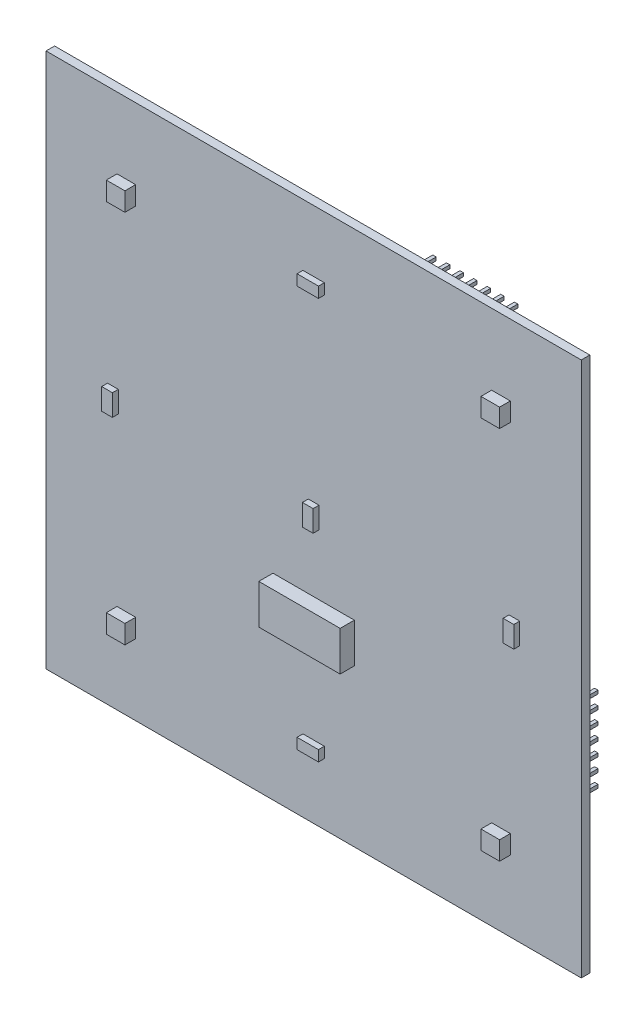
SolidWorks part; units mm, degrees
ref_plane "正面" through (0, 0, 0) normal (0, 0, 1) x (1, 0, 0)
ref_plane "平面" through (0, 0, 0) normal (0, 1, 0) x (1, 0, 0)
ref_plane "右側面" through (0, 0, 0) normal (1, 0, 0) x (0, 0, -1)
sketch "ｽｹｯﾁ1" plane through (0, 0, 0) normal (0, 0, 1) x (1, 0, 0)
  line L0 (-50, 0) -> (50, 0) construction
  line L1 (-50, 50) -> (50, 50)
  line L2 (-50, 50) -> (-50, -50)
  line L3 (-50, -50) -> (50, -50)
  line L4 (50, 50) -> (50, -50)
  line L5 (0, -50) -> (0, 50) construction
  point P8 (0, 0)
  dimension "D1" = 100
  dimension "D2" = 100
  dimension "D3" = 0
  dimension "D4" = 0
extrude "ﾎﾞｽ - 押し出し1" add sketch "ｽｹｯﾁ1" along normal blind 1.6
sketch "ｽｹｯﾁ4" plane through (0, 0, 0) normal (0, 0, -1) x (-1, 0, 0)
  line L0 (-50, -50) -> (-50, 50) construction
  line L1 (11.11, -41.35) -> (28.89, -41.35)
  line L2 (11.11, -41.35) -> (11.11, -43.85)
  line L3 (11.11, -43.85) -> (28.89, -43.85)
  line L4 (28.89, -41.35) -> (28.89, -43.85)
  line L5 (50, -50) -> (-50, -50) construction
  line L6 (50, 50) -> (50, -50) construction
  line L8 (-43.85, -11.11) -> (-41.35, -11.11)
  line L9 (-43.85, -11.11) -> (-43.85, -28.89)
  line L10 (-43.85, -28.89) -> (-41.35, -28.89)
  line L11 (-41.35, -11.11) -> (-41.35, -28.89)
  line L12 (-28.89, 43.85) -> (-11.11, 43.85)
  line L13 (-28.89, 43.85) -> (-28.89, 41.35)
  line L14 (-28.89, 41.35) -> (-11.11, 41.35)
  line L15 (-11.11, 43.85) -> (-11.11, 41.35)
  line L16 (-50, 50) -> (50, 50) construction
  line L18 (41.35, 28.89) -> (43.85, 28.89)
  line L19 (41.35, 28.89) -> (41.35, 11.11)
  line L20 (41.35, 11.11) -> (43.85, 11.11)
  line L21 (43.85, 28.89) -> (43.85, 11.11)
  point P4 (28.89, -42.6)
  point P7 (20, -43.85)
  point P14 (-43.85, -20)
  point P15 (-42.6, -28.89)
  point P22 (-28.89, 42.6)
  point P25 (43.85, 20)
  point P26 (-20, 43.85)
  point P31 (42.6, 28.89)
  dimension "D1" = 7.4
  dimension "D2" = 30
  dimension "D3" = 2.5
  dimension "D4" = 17.78
  dimension "D5" = 2.5
  dimension "D6" = 17.78
  dimension "D7" = 30
  dimension "D8" = 7.4
  dimension "D9" = 2.5
  dimension "D10" = 7.4
  dimension "D11" = 30
  dimension "D12" = 17.78
  dimension "D13" = 17.78
  dimension "D14" = 2.5
  dimension "D15" = 30
  dimension "D16" = 7.4
extrude "ﾎﾞｽ - 押し出し2" add sketch "ｽｹｯﾁ4" along normal blind 2.5
sketch "ｽｹｯﾁ5" plane through (0, 0, -2.5) normal (0, 0, -1) x (-1, 0, 0)
  line L1 (-20.32, 42.92) -> (-19.68, 42.92)
  line L2 (-20.32, 42.92) -> (-20.32, 42.28)
  line L3 (-20.32, 42.28) -> (-19.68, 42.28)
  line L4 (-19.68, 42.92) -> (-19.68, 42.28)
  line L5 (43.85, 28.89) -> (41.35, 28.89) construction
  line L6 (-11.11, 43.85) -> (-28.89, 43.85) construction
  line L7 (-28.89, 43.85) -> (-28.89, 41.35) construction
  line L8 (-43.85, -28.89) -> (-41.35, -28.89) construction
  line L9 (-17.78, 42.92) -> (-17.14, 42.92)
  line L10 (-17.78, 42.92) -> (-17.78, 42.28)
  line L11 (-17.78, 42.28) -> (-17.14, 42.28)
  line L12 (-17.14, 42.92) -> (-17.14, 42.28)
  line L13 (-15.24, 42.92) -> (-14.6, 42.92)
  line L14 (-15.24, 42.92) -> (-15.24, 42.28)
  line L15 (-15.24, 42.28) -> (-14.6, 42.28)
  line L16 (-14.6, 42.92) -> (-14.6, 42.28)
  line L17 (-12.7, 42.92) -> (-12.06, 42.92)
  line L18 (-12.7, 42.92) -> (-12.7, 42.28)
  line L19 (-12.7, 42.28) -> (-12.06, 42.28)
  line L20 (-12.06, 42.92) -> (-12.06, 42.28)
  line L21 (-22.86, 42.92) -> (-22.22, 42.92)
  line L22 (-22.86, 42.92) -> (-22.86, 42.28)
  line L23 (-22.86, 42.28) -> (-22.22, 42.28)
  line L24 (-22.22, 42.92) -> (-22.22, 42.28)
  line L25 (-25.4, 42.92) -> (-24.76, 42.92)
  line L26 (-25.4, 42.92) -> (-25.4, 42.28)
  line L27 (-25.4, 42.28) -> (-24.76, 42.28)
  line L28 (-24.76, 42.92) -> (-24.76, 42.28)
  line L29 (-27.94, 42.92) -> (-27.3, 42.92)
  line L30 (-27.94, 42.92) -> (-27.94, 42.28)
  line L31 (-27.94, 42.28) -> (-27.3, 42.28)
  line L32 (-27.3, 42.92) -> (-27.3, 42.28)
  line L33 (-42.92, -19.68) -> (-42.28, -19.68)
  line L34 (-42.92, -19.68) -> (-42.92, -20.32)
  line L35 (-42.92, -20.32) -> (-42.28, -20.32)
  line L36 (-42.28, -19.68) -> (-42.28, -20.32)
  line L37 (-43.85, -11.11) -> (-43.85, -28.89) construction
  line L38 (43.85, 11.11) -> (43.85, 28.89) construction
  line L39 (-42.92, -22.22) -> (-42.28, -22.22)
  line L40 (-42.92, -22.22) -> (-42.92, -22.86)
  line L41 (-42.92, -22.86) -> (-42.28, -22.86)
  line L42 (-42.28, -22.22) -> (-42.28, -22.86)
  line L44 (42.28, 19.68) -> (42.92, 19.68)
  line L45 (-42.92, -24.76) -> (-42.28, -24.76)
  line L46 (-42.92, -24.76) -> (-42.92, -25.4)
  line L47 (-42.92, -25.4) -> (-42.28, -25.4)
  line L48 (-42.28, -24.76) -> (-42.28, -25.4)
  line L49 (-42.92, -27.3) -> (-42.28, -27.3)
  line L50 (-42.92, -27.3) -> (-42.92, -27.94)
  line L51 (-42.92, -27.94) -> (-42.28, -27.94)
  line L52 (-42.28, -27.3) -> (-42.28, -27.94)
  line L53 (-42.92, -17.14) -> (-42.28, -17.14)
  line L54 (-42.92, -17.14) -> (-42.92, -17.78)
  line L55 (-42.92, -17.78) -> (-42.28, -17.78)
  line L56 (-42.28, -17.14) -> (-42.28, -17.78)
  line L57 (-42.92, -14.6) -> (-42.28, -14.6)
  line L58 (-42.92, -14.6) -> (-42.92, -15.24)
  line L59 (-42.92, -15.24) -> (-42.28, -15.24)
  line L60 (-42.28, -14.6) -> (-42.28, -15.24)
  line L61 (-42.92, -12.06) -> (-42.28, -12.06)
  line L62 (-42.92, -12.06) -> (-42.92, -12.7)
  line L63 (-42.92, -12.7) -> (-42.28, -12.7)
  line L64 (-42.28, -12.06) -> (-42.28, -12.7)
  line L69 (42.28, 19.68) -> (42.28, 20.32)
  line L70 (11.11, -43.85) -> (28.89, -43.85) construction
  line L71 (42.28, 17.78) -> (42.92, 17.78)
  line L72 (42.28, 20.32) -> (42.92, 20.32)
  line L73 (42.92, 19.68) -> (42.92, 20.32)
  line L75 (42.28, 17.78) -> (42.28, 17.14)
  line L76 (42.28, 17.14) -> (42.92, 17.14)
  line L77 (42.92, 17.78) -> (42.92, 17.14)
  line L78 (42.28, 15.24) -> (42.92, 15.24)
  line L79 (42.28, 15.24) -> (42.28, 14.6)
  line L80 (42.28, 14.6) -> (42.92, 14.6)
  line L81 (42.92, 15.24) -> (42.92, 14.6)
  line L82 (42.28, 12.7) -> (42.92, 12.7)
  line L83 (42.28, 12.7) -> (42.28, 12.06)
  line L84 (42.28, 12.06) -> (42.92, 12.06)
  line L85 (42.92, 12.7) -> (42.92, 12.06)
  line L86 (42.28, 22.86) -> (42.92, 22.86)
  line L87 (42.28, 22.86) -> (42.28, 22.22)
  line L88 (42.28, 22.22) -> (42.92, 22.22)
  line L89 (42.92, 22.86) -> (42.92, 22.22)
  line L90 (42.28, 25.4) -> (42.92, 25.4)
  line L91 (42.28, 25.4) -> (42.28, 24.76)
  line L92 (42.28, 24.76) -> (42.92, 24.76)
  line L93 (42.92, 25.4) -> (42.92, 24.76)
  line L94 (42.28, 27.94) -> (42.92, 27.94)
  line L95 (42.28, 27.94) -> (42.28, 27.3)
  line L96 (42.28, 27.3) -> (42.92, 27.3)
  line L97 (42.92, 27.94) -> (42.92, 27.3)
  line L98 (19.68, -42.28) -> (20.32, -42.28)
  line L99 (19.68, -42.28) -> (19.68, -42.92)
  line L100 (19.68, -42.92) -> (20.32, -42.92)
  line L101 (20.32, -42.28) -> (20.32, -42.92)
  line L102 (11.11, -41.35) -> (11.11, -43.85) construction
  line L104 (17.14, -42.28) -> (17.78, -42.28)
  line L105 (17.14, -42.28) -> (17.14, -42.92)
  line L106 (17.14, -42.92) -> (17.78, -42.92)
  line L107 (17.78, -42.28) -> (17.78, -42.92)
  line L108 (14.6, -42.28) -> (15.24, -42.28)
  line L109 (14.6, -42.28) -> (14.6, -42.92)
  line L110 (14.6, -42.92) -> (15.24, -42.92)
  line L111 (15.24, -42.28) -> (15.24, -42.92)
  line L112 (12.06, -42.28) -> (12.7, -42.28)
  line L113 (12.06, -42.28) -> (12.06, -42.92)
  line L114 (12.06, -42.92) -> (12.7, -42.92)
  line L115 (12.7, -42.28) -> (12.7, -42.92)
  line L116 (22.22, -42.28) -> (22.86, -42.28)
  line L117 (22.22, -42.28) -> (22.22, -42.92)
  line L118 (22.22, -42.92) -> (22.86, -42.92)
  line L119 (22.86, -42.28) -> (22.86, -42.92)
  line L120 (24.76, -42.28) -> (25.4, -42.28)
  line L121 (24.76, -42.28) -> (24.76, -42.92)
  line L122 (24.76, -42.92) -> (25.4, -42.92)
  line L123 (25.4, -42.28) -> (25.4, -42.92)
  line L124 (27.3, -42.28) -> (27.94, -42.28)
  line L125 (27.3, -42.28) -> (27.3, -42.92)
  line L126 (27.3, -42.92) -> (27.94, -42.92)
  line L127 (27.94, -42.28) -> (27.94, -42.92)
  point P4 (-20, 42.92)
  point P7 (-20, 43.85)
  point P8 (-20.32, 42.6)
  point P11 (-28.89, 42.6)
  point P16 (-20, 42.28)
  point P17 (-17.46, 42.28)
  point P22 (-14.92, 42.28)
  point P27 (-12.38, 42.28)
  point P40 (-22.54, 42.28)
  point P41 (-25.08, 42.28)
  point P42 (-27.62, 42.28)
  point P47 (-42.6, -20.32)
  point P50 (-42.6, -28.89)
  point P53 (-42.92, -20)
  point P54 (-43.85, -20)
  point P59 (-42.28, -22.54)
  point P60 (-42.28, -20)
  point P61 (-42.28, -25.08)
  point P70 (-42.28, -27.62)
  point P83 (-42.28, -17.46)
  point P84 (-42.28, -14.92)
  point P85 (-42.28, -12.38)
  point P90 (42.6, 19.68)
  point P93 (42.6, 28.89)
  point P94 (42.92, 20)
  point P97 (43.85, 20)
  point P110 (42.28, 12.38)
  point P111 (42.28, 14.92)
  point P112 (42.28, 17.46)
  point P113 (42.28, 20)
  point P126 (42.28, 22.54)
  point P127 (42.28, 25.08)
  point P128 (42.28, 27.62)
  point P133 (20, -42.92)
  point P136 (20, -43.85)
  point P139 (11.11, -42.6)
  point P140 (19.68, -42.6)
  point P165 (17.46, -42.28)
  point P166 (20, -42.28)
  point P167 (14.92, -42.28)
  point P168 (12.38, -42.28)
  point P169 (22.54, -42.28)
  point P170 (25.08, -42.28)
  point P171 (27.62, -42.28)
  point P173 (12.06, -42.6)
  point P174 (14.6, -42.6)
  point P175 (17.14, -42.6)
  point P176 (22.22, -42.6)
  point P177 (24.76, -42.6)
  point P178 (27.3, -42.6)
  point P179 (-42.6, -27.3)
  point P180 (-42.6, -24.76)
  point P181 (-42.6, -22.22)
  point P182 (-42.6, -19.68)
  point P183 (-42.6, -17.14)
  point P184 (-42.6, -14.6)
  point P185 (-42.6, -12.06)
  point P186 (-27.94, 42.6)
  point P187 (-25.4, 42.6)
  point P188 (-22.86, 42.6)
  point P189 (-17.78, 42.6)
  point P190 (-15.24, 42.6)
  point P191 (-12.7, 42.6)
  point P192 (42.6, 15.24)
  point P193 (42.6, 17.78)
  point P194 (42.6, 20.32)
  point P195 (42.6, 22.86)
  point P196 (42.6, 25.4)
  point P197 (42.6, 27.94)
  point P198 (42.6, 12.7)
  dimension "D1" = 0.64
  dimension "D2" = 0.64
  dimension "D3" = 0.64
  dimension "D4" = 0.64
  dimension "D5" = 2.54
  dimension "D6" = 0.64
  dimension "D7" = 2.54
  dimension "D8" = 0.64
  dimension "D9" = 0.64
  dimension "D10" = 0.64
  dimension "D11" = 2.54
  dimension "D12" = 0.64
  dimension "D13" = 0.64
  dimension "D14" = 0.64
  dimension "D15" = 2.54
  dimension "D16" = 0.64
  dimension "D17" = 0.64
  dimension "D18" = 0.64
  dimension "D19" = 2.54
  dimension "D20" = 2.54
  dimension "D21" = 0.64
  dimension "D22" = 0.64
  dimension "D23" = 0.64
  dimension "D24" = 0.64
  dimension "D25" = 2.54
  dimension "D26" = 0.64
  dimension "D27" = 2.54
  dimension "D28" = 0.64
  dimension "D29" = 2.54
  dimension "D30" = 0.64
  dimension "D31" = 0.64
  dimension "D32" = 0.64
  dimension "D33" = 0.64
  dimension "D34" = 2.54
  dimension "D35" = 2.54
  dimension "D36" = 0.64
  dimension "D37" = 0.64
  dimension "D38" = 0.64
  dimension "D39" = 2.54
  dimension "D40" = 0.64
  dimension "D41" = 0.64
  dimension "D42" = 0.64
  dimension "D43" = 0.64
  dimension "D44" = 0.64
  dimension "D45" = 0.64
  dimension "D46" = 2.54
  dimension "D47" = 2.54
  dimension "D48" = 2.54
  dimension "D49" = 2.54
  dimension "D50" = 0.64
  dimension "D51" = 0.64
  dimension "D52" = 0.64
  dimension "D53" = 0.64
  dimension "D54" = 2.54
  dimension "D55" = 0.64
  dimension "D56" = 0.64
  dimension "D57" = 2.54
  dimension "D58" = 0.64
  dimension "D59" = 0.64
  dimension "D60" = 0.64
  dimension "D61" = 0.64
  dimension "D62" = 0.64
  dimension "D63" = 2.54
  dimension "D64" = 2.54
  dimension "D65" = 2.54
  dimension "D66" = 0.64
  dimension "D67" = 0.64
  dimension "D68" = 0.64
  dimension "D69" = 0.64
  dimension "D70" = 0.64
  dimension "D71" = 0.64
  dimension "D72" = 2.54
  dimension "D73" = 2.54
  dimension "D74" = 2.54
  dimension "D75" = 0.64
  dimension "D76" = 0.64
  dimension "D77" = 0.64
  dimension "D78" = 0.64
  dimension "D79" = 0.64
  dimension "D80" = 0.64
extrude "ﾎﾞｽ - 押し出し3" add sketch "ｽｹｯﾁ5" along normal blind 6.1
sketch "ｽｹｯﾁ6" plane through (0, 0, 1.6) normal (0, 0, 1) x (1, 0, 0)
  line L0 (-50, -50) -> (50, -50) construction
  line L1 (-36.74, -33.26) -> (-33.26, -33.26)
  line L2 (-36.74, -33.26) -> (-36.74, -36.74)
  line L3 (-36.74, -36.74) -> (-33.26, -36.74)
  line L4 (-33.26, -33.26) -> (-33.26, -36.74)
  line L5 (-50, 50) -> (-50, -50) construction
  line L6 (50, 50) -> (-50, 50) construction
  line L7 (-36.74, 36.74) -> (-33.26, 36.74)
  line L8 (-36.74, 36.74) -> (-36.74, 33.26)
  line L9 (-36.74, 33.26) -> (-33.26, 33.26)
  line L10 (-33.26, 36.74) -> (-33.26, 33.26)
  line L11 (50, -50) -> (50, 50) construction
  line L12 (33.26, -33.26) -> (36.74, -33.26)
  line L13 (33.26, -33.26) -> (33.26, -36.74)
  line L14 (33.26, -36.74) -> (36.74, -36.74)
  line L15 (36.74, -33.26) -> (36.74, -36.74)
  line L17 (33.26, 36.74) -> (36.74, 36.74)
  line L18 (33.26, 36.74) -> (33.26, 33.26)
  line L19 (33.26, 33.26) -> (36.74, 33.26)
  line L20 (36.74, 36.74) -> (36.74, 33.26)
  point P4 (-36.74, -35)
  point P7 (-35, -36.74)
  point P14 (-36.74, 35)
  point P17 (-35, 36.74)
  point P22 (35, -36.74)
  point P25 (36.74, -35)
  point P30 (35, 36.74)
  point P31 (36.74, 35)
  dimension "D1" = 3.48
  dimension "D2" = 3.48
  dimension "D3" = 15
  dimension "D4" = 15
  dimension "D5" = 3.48
  dimension "D6" = 3.48
  dimension "D7" = 15
  dimension "D8" = 15
  dimension "D9" = 15
  dimension "D10" = 15
  dimension "D11" = 3.48
  dimension "D12" = 3.48
  dimension "D13" = 15
  dimension "D14" = 15
  dimension "D15" = 3.48
  dimension "D16" = 3.48
extrude "ﾎﾞｽ - 押し出し4" add sketch "ｽｹｯﾁ6" along normal blind 2
sketch "ｽｹｯﾁ7" plane through (0, 0, 1.6) normal (0, 0, 1) x (1, 0, 0)
  line L0 (-50, -50) -> (50, -50) construction
  line L1 (-38.5, 2) -> (-36.5, 2)
  line L2 (-38.5, 2) -> (-38.5, -2)
  line L3 (-38.5, -2) -> (-36.5, -2)
  line L4 (-36.5, 2) -> (-36.5, -2)
  line L5 (-50, 50) -> (-50, -50) construction
  line L6 (50, -50) -> (50, 50) construction
  line L7 (36.5, 2) -> (38.5, 2)
  line L8 (36.5, 2) -> (36.5, -2)
  line L9 (36.5, -2) -> (38.5, -2)
  line L10 (38.5, 2) -> (38.5, -2)
  line L11 (50, 50) -> (-50, 50) construction
  line L12 (-2, 38.5) -> (2, 38.5)
  line L13 (-2, 38.5) -> (-2, 36.5)
  line L14 (-2, 36.5) -> (2, 36.5)
  line L15 (2, 38.5) -> (2, 36.5)
  line L17 (-2, -36.5) -> (2, -36.5)
  line L18 (-2, -36.5) -> (-2, -38.5)
  line L19 (-2, -38.5) -> (2, -38.5)
  line L20 (2, -36.5) -> (2, -38.5)
  line L21 (-1, 2) -> (1, 2)
  line L22 (-1, 2) -> (-1, -2)
  line L23 (-1, -2) -> (1, -2)
  line L24 (1, 2) -> (1, -2)
  point P4 (-38.5, 0)
  point P7 (-37.5, -2)
  point P14 (37.5, 2)
  point P17 (38.5, 0)
  point P22 (-2, 37.5)
  point P25 (0, 38.5)
  point P30 (-2, -37.5)
  point P31 (0, -38.5)
  point P36 (1, 0)
  point P37 (36.5, 0)
  point P38 (0, 36.5)
  point P39 (0, 2)
  dimension "D1" = 4
  dimension "D2" = 2
  dimension "D3" = 50
  dimension "D4" = 12.5
  dimension "D5" = 4
  dimension "D6" = 2
  dimension "D7" = 12.5
  dimension "D8" = 50
  dimension "D9" = 4
  dimension "D10" = 2
  dimension "D11" = 12.5
  dimension "D12" = 50
  dimension "D13" = 4
  dimension "D14" = 2
  dimension "D15" = 12.5
  dimension "D16" = 50
  dimension "D17" = 4
  dimension "D18" = 2
extrude "ﾎﾞｽ - 押し出し5" add sketch "ｽｹｯﾁ7" along normal blind 1.1
sketch "ｽｹｯﾁ8" plane through (0, 0, 1.6) normal (0, 0, 1) x (1, 0, 0)
  line L0 (-50, -50) -> (50, -50) construction
  line L1 (-7.6, -13.3) -> (7.6, -13.3)
  line L2 (-7.6, -13.3) -> (-7.6, -20.7)
  line L3 (-7.6, -20.7) -> (7.6, -20.7)
  line L4 (7.6, -13.3) -> (7.6, -20.7)
  point P4 (-7.6, -17)
  point P7 (0, -50)
  point P8 (0, -20.7)
  dimension "D1" = 7.4
  dimension "D2" = 15.2
  dimension "D3" = 33
extrude "ﾎﾞｽ - 押し出し6" add sketch "ｽｹｯﾁ8" along normal blind 2.65
sketch "ｽｹｯﾁ9" plane through (0, 0, 0) normal (0, 0, -1) x (-1, 0, 0)
  line L1 (-4.61, 19.83) -> (3.01, 19.83)
  line L2 (-4.61, 19.83) -> (-4.61, 17.33)
  line L3 (-4.61, 17.33) -> (3.01, 17.33)
  line L4 (3.01, 19.83) -> (3.01, 17.33)
  line L5 (50, 50) -> (50, -50) construction
  line L6 (50, -50) -> (-50, -50) construction
  point P4 (-0.8, 19.83)
  point P7 (3.01, 18.58)
  dimension "D1" = 7.62
  dimension "D2" = 2.5
  dimension "D3" = 50.8
  dimension "D4" = 68.58
extrude "ﾎﾞｽ - 押し出し7" add sketch "ｽｹｯﾁ9" along normal blind 2.5
sketch "ｽｹｯﾁ11" plane through (0, 0, -2.5) normal (0, 0, -1) x (-1, 0, 0)
  line L0 (3.01, 19.83) -> (-4.61, 19.83) construction
  line L1 (-1.12, 18.9) -> (-0.48, 18.9)
  line L2 (-1.12, 18.9) -> (-1.12, 18.26)
  line L3 (-1.12, 18.26) -> (-0.48, 18.26)
  line L4 (-0.48, 18.9) -> (-0.48, 18.26)
  line L5 (-4.61, 19.83) -> (-4.61, 17.33) construction
  line L7 (-3.66, 18.9) -> (-3.02, 18.9)
  line L8 (-3.66, 18.9) -> (-3.66, 18.26)
  line L9 (-3.66, 18.26) -> (-3.02, 18.26)
  line L10 (-3.02, 18.9) -> (-3.02, 18.26)
  line L11 (1.42, 18.9) -> (2.06, 18.9)
  line L12 (1.42, 18.9) -> (1.42, 18.26)
  line L13 (1.42, 18.26) -> (2.06, 18.26)
  line L14 (2.06, 18.9) -> (2.06, 18.26)
  point P4 (-0.8, 18.9)
  point P7 (-0.8, 19.83)
  point P8 (-1.12, 18.58)
  point P11 (-4.61, 18.58)
  point P20 (-3.34, 18.26)
  point P21 (-0.8, 18.26)
  point P22 (1.74, 18.26)
  point P23 (-3.66, 18.58)
  point P25 (1.42, 18.58)
  dimension "D1" = 0.64
  dimension "D2" = 0.64
  dimension "D3" = 0.64
  dimension "D4" = 0.64
  dimension "D5" = 0.64
  dimension "D6" = 2.54
  dimension "D7" = 2.54
extrude "ﾎﾞｽ - 押し出し8" add sketch "ｽｹｯﾁ11" along normal blind 6.1
sketch "ｽｹｯﾁ13" plane through (0, 0, 0) normal (0, 0, -1) x (-1, 0, 0)
  line L0 (-50, -50) -> (-50, 50) construction
  line L7 (-50, 50) -> (50, 50) construction
  line L8 (50, -50) -> (-50, -50) construction
  line L15 (50, 50) -> (50, -50) construction
  line L23 (32, -30) -> (31, -28.2679)
  line L24 (31, -28.2679) -> (29, -28.2679)
  line L25 (29, -28.2679) -> (28, -30)
  line L26 (28, -30) -> (29, -31.7321)
  line L27 (29, -31.7321) -> (31, -31.7321)
  line L28 (31, -31.7321) -> (32, -30)
  line L29 (-28, -30) -> (-29, -28.2679)
  line L30 (-29, -28.2679) -> (-31, -28.2679)
  line L31 (-31, -28.2679) -> (-32, -30)
  line L32 (-32, -30) -> (-31, -31.7321)
  line L33 (-31, -31.7321) -> (-29, -31.7321)
  line L34 (-29, -31.7321) -> (-28, -30)
  line L35 (32, 30) -> (31, 31.7321)
  line L36 (31, 31.7321) -> (29, 31.7321)
  line L37 (29, 31.7321) -> (28, 30)
  line L38 (28, 30) -> (29, 28.2679)
  line L39 (29, 28.2679) -> (31, 28.2679)
  line L40 (31, 28.2679) -> (32, 30)
  line L41 (-28, 30) -> (-29, 31.7321)
  line L42 (-29, 31.7321) -> (-31, 31.7321)
  line L43 (-31, 31.7321) -> (-32, 30)
  line L44 (-32, 30) -> (-31, 28.2679)
  line L45 (-31, 28.2679) -> (-29, 28.2679)
  line L46 (-29, 28.2679) -> (-28, 30)
  circle A0 centre (-30, 30) radius 2 construction
  circle A1 centre (-30, -30) radius 2 construction
  circle A2 centre (30, 30) radius 2 construction
  circle A3 centre (30, -30) radius 2 construction
  dimension "D1" = 20
  dimension "D2" = 20
  dimension "D3" = 20
  dimension "D4" = 20
  dimension "D5" = 20
  dimension "D6" = 20
  dimension "D7" = 20
  dimension "D8" = 20
extrude "ﾎﾞｽ - 押し出し9" add sketch "ｽｹｯﾁ13" along normal blind 6
sketch "ｽｹｯﾁ14" plane through (0, 0, -6) normal (0, 0, -1) x (-1, 0, 0)
  line L2 (0, -39) -> (0, -41)
  line L3 (0, -41) -> (39, -41)
  line L4 (39, -41) -> (39, 0)
  line L5 (39, 0) -> (41, 0)
  line L6 (41, 0) -> (41, 39)
  line L7 (41, 39) -> (0, 39)
  line L8 (0, 39) -> (0, 41)
  line L9 (0, 41) -> (-39, 41)
  line L11 (-39, 41) -> (-39, 0)
  line L12 (-39, 0) -> (-41, 0)
  line L13 (-41, 0) -> (-41, -39)
  line L14 (-41, -39) -> (0, -39)
  line L21 (-29, 31.7321) -> (-31, 31.7321) construction
  line L22 (-4.61, 19.83) -> (3.01, 19.83)
  line L23 (-4.61, 19.83) -> (-4.61, 17.33)
  line L24 (-4.61, 17.33) -> (3.01, 17.33)
  line L25 (3.01, 19.83) -> (3.01, 17.33)
  line L26 (31, 31.7321) -> (29, 31.7321) construction
  line L27 (31, -28.2679) -> (29, -28.2679) construction
  line L28 (-29, -28.2679) -> (-31, -28.2679) construction
  circle A0 centre (-30, 30) radius 1
  circle A1 centre (30, 30) radius 1
  circle A2 centre (30, -30) radius 1
  circle A3 centre (-30, -30) radius 1
  point P28 (-30, 31.7321)
  point P37 (30, 31.7321)
  point P41 (30, -28.2679)
  point P47 (-30, -28.2679)
  dimension "D1" = 39
  dimension "D2" = 41
  dimension "D3" = 41
  dimension "D4" = 39
  dimension "D5" = 41
  dimension "D6" = 39
  dimension "D7" = 41
  dimension "D8" = 39
  dimension "D9" = 2.5
  dimension "D10" = 7.62
extrude "ﾎﾞｽ - 押し出し10" add sketch "ｽｹｯﾁ14" along normal blind 2 separate body
